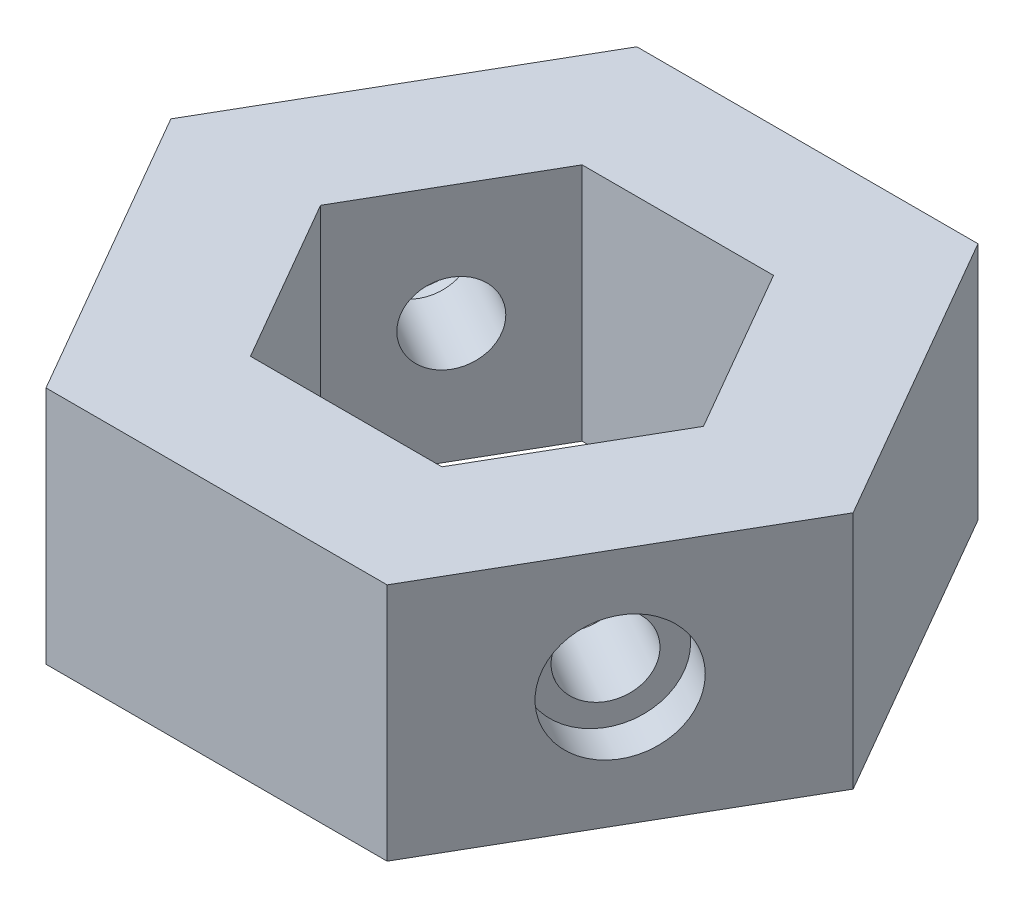
SolidWorks part; units mm, degrees
ref_plane "Front Plane" through (0, 0, 0) normal (0, 0, 1) x (1, 0, 0)
ref_plane "Top Plane" through (0, 0, 0) normal (0, 1, 0) x (1, 0, 0)
ref_plane "Right Plane" through (0, 0, 0) normal (1, 0, 0) x (0, 0, -1)
sketch "Sketch1" plane through (0, 0, 0) normal (0, 1, 0) x (1, 0, 0)
  line L1 (7.62, 0) -> (3.81, 6.5991)
  line L2 (3.81, 6.5991) -> (-3.81, 6.5991)
  line L3 (-3.81, 6.5991) -> (-7.62, 0)
  line L4 (-7.62, 0) -> (-3.81, -6.5991)
  line L5 (-3.81, -6.5991) -> (3.81, -6.5991)
  line L6 (3.81, -6.5991) -> (7.62, 0)
  line L7 (13.5775, 0) -> (6.7888, 11.7585)
  line L8 (6.7888, 11.7585) -> (-6.7888, 11.7585)
  line L9 (-6.7888, 11.7585) -> (-13.5775, 0)
  line L10 (-13.5775, 0) -> (-6.7888, -11.7585)
  line L11 (-6.7888, -11.7585) -> (6.7888, -11.7585)
  line L12 (6.7888, -11.7585) -> (13.5775, 0)
  circle A0 centre (0, 0) radius 6.5991 construction
  circle A1 centre (0, 0) radius 11.7585 construction
  dimension "D1" = 7.62
  dimension "D2" = 5.1594
extrude "Boss-Extrude1" add sketch "Sketch1" along normal blind 9.525
sketch "Sketch2" plane through (10.1831, 0, 5.8792) normal (0.866, 0, 0.5) x (0.5, 0, -0.866)
  line L0 (-6.7888, 9.525) -> (6.7888, 9.525) construction
  circle A0 centre (0, 4.7625) radius 2.4805
  dimension "D1" = 4.7625
extrude "Cut-Extrude1" cut sketch "Sketch2" against normal blind 1.5875
sketch "Sketch3" plane through (8.8083, 0, 5.0855) normal (0.866, 0, 0.5) x (0.5, 0, -0.866)
  line L0 (-6.7888, 9.525) -> (6.7888, 9.525) construction
  circle A0 centre (0, 4.7625) radius 1.5875
  dimension "D1" = 4.7625
extrude "Cut-Extrude2" cut sketch "Sketch3" against normal blind 6.35
sketch "Sketch4" plane through (-10.1831, 0, -5.8792) normal (-0.866, 0, -0.5) x (-0.5, 0, 0.866)
  line L0 (-6.7888, 9.525) -> (6.7888, 9.525) construction
  circle A0 centre (0, 4.7625) radius 2.4576
  dimension "D1" = 4.7625
  dimension "D2" = 4.9152
extrude "Cut-Extrude3" cut sketch "Sketch4" against normal blind 1.5875
sketch "Sketch5" plane through (-8.8083, 0, -5.0855) normal (-0.866, 0, -0.5) x (-0.5, 0, 0.866)
  circle A0 centre (0, 4.7625) radius 1.5875
extrude "Cut-Extrude4" cut sketch "Sketch5" against normal blind 6.35 contours A0
